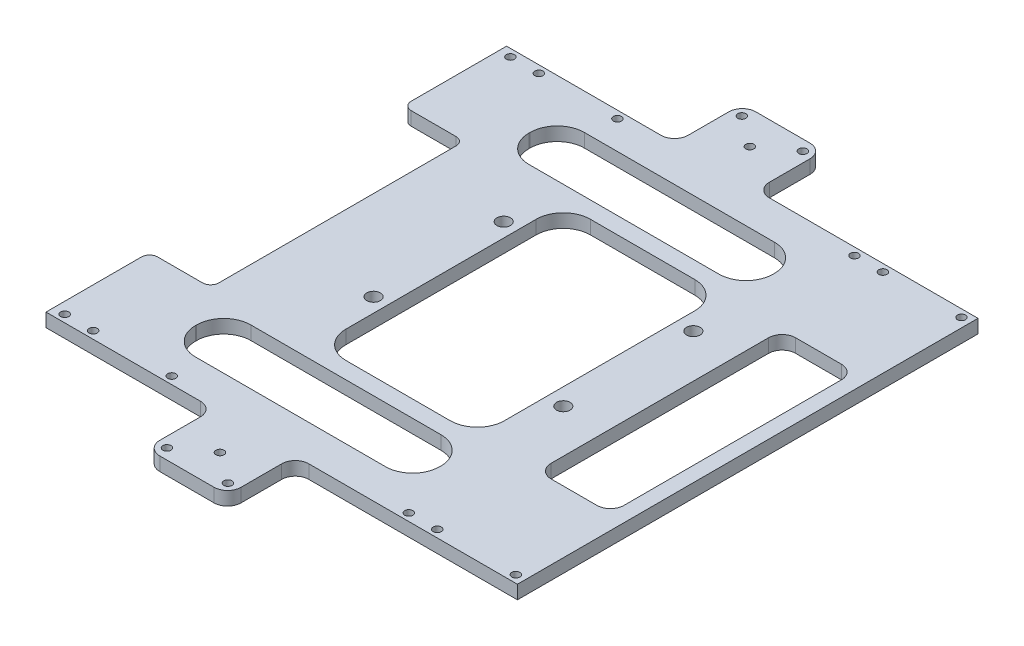
SolidWorks part; units mm, degrees
ref_plane "前视基准面" through (0, 0, 0) normal (0, 0, 1) x (1, 0, 0)
ref_plane "上视基准面" through (0, 0, 0) normal (0, 1, 0) x (1, 0, 0)
ref_plane "右视基准面" through (0, 0, 0) normal (1, 0, 0) x (0, 0, -1)
other "Configuration Table"
sketch "草图1" plane through (0, 0, 0) normal (0, 1, 0) x (1, 0, 0)
  line L0 (0, 0) -> (179.4567, 0) construction
  line L1 (-150, 150) -> (150, 150) construction
  line L2 (-150, 150) -> (-150, -150) construction
  line L3 (-150, -150) -> (150, -150) construction
  line L4 (150, 150) -> (150, -150) construction
  line L5 (-150, 150) -> (150, -150) construction
  line L6 (-150, -150) -> (150, 150) construction
  line L7 (-125, 85) -> (-67.9992, 85)
  line L9 (-125, -85) -> (-67.9992, -85)
  line L11 (-125, 85) -> (-125, 46.7806)
  line L16 (-111.5, 85) -> (-111.5, -49915) construction
  line L17 (-27.9992, 85) -> (49.0008, 85)
  line L29 (-62.9992, 90) -> (-62.9992, 105)
  line L30 (-57.9992, 110) -> (-37.9992, 110)
  line L31 (-32.9992, 90) -> (-32.9992, 105)
  line L32 (-32.9992, -90) -> (-32.9992, -105)
  line L33 (-57.9992, -110) -> (-37.9992, -110)
  line L34 (-62.9992, -90) -> (-62.9992, -105)
  line L35 (-27.9992, -85) -> (49.0008, -85)
  line L44 (15.5008, 96) -> (15.5008, -352.075) construction
  line L46 (-144.9992, -88.2675) -> (-77.9992, -88.2675) construction
  line L47 (-144.9992, -88.2675) -> (-144.9992, -128.3094) construction
  line L48 (-144.9992, -128.3094) -> (-77.9992, -128.3094) construction
  line L49 (-77.9992, -88.2675) -> (-77.9992, -128.3094) construction
  line L57 (-77.9992, 88.2675) -> (-77.9992, 128.3094) construction
  line L58 (-144.9992, 128.3094) -> (-77.9992, 128.3094) construction
  line L59 (-144.9992, 88.2675) -> (-144.9992, 128.3094) construction
  line L60 (-144.9992, 88.2675) -> (-77.9992, 88.2675) construction
  line L61 (-17.9992, -88.2675) -> (-17.9992, -128.3) construction
  line L62 (49.0008, -128.3) -> (-17.9992, -128.3) construction
  line L63 (49.0008, 128.3) -> (-17.9992, 128.3) construction
  line L64 (49.0008, 88.2675) -> (-17.9992, 88.2675) construction
  line L65 (49.0008, 88.2675) -> (49.0008, 128.3) construction
  line L66 (49.0008, 128.3) -> (-17.9992, 128.3) construction
  line L67 (-17.9992, 88.2675) -> (-17.9992, 128.3) construction
  line L68 (49.0008, -88.2675) -> (49.0008, -128.3) construction
  line L69 (49.0008, -88.2675) -> (-17.9992, -88.2675) construction
  line L71 (-47.9992, 110) -> (-47.9992, -134.4619) construction
  line L72 (49.0008, 85) -> (49.0008, -85)
  line L73 (-12.9149, -51.3108) -> (-83.0835, -51.3108)
  line L74 (-12.9149, 71.7703) -> (-83.0835, 71.7703)
  line L75 (-2.9149, 61.7703) -> (-2.9149, 61.3108)
  line L76 (-12.9149, 51.3108) -> (-83.0835, 51.3108)
  line L77 (-93.0835, 61.7703) -> (-93.0835, 61.3108)
  line L78 (-93.0835, -61.7703) -> (-93.0835, -61.3108)
  line L79 (-2.9149, -61.7703) -> (-2.9149, -61.3108)
  line L80 (-12.9149, -71.7703) -> (-83.0835, -71.7703)
  line L81 (-69.4223, 28.3555) -> (-69.4223, -19.6445) construction
  line L82 (-15.666, 45.1305) -> (-54.2, 45.1305)
  line L83 (-5.666, 35.1305) -> (-5.666, -35.1305)
  line L84 (-15.666, -45.1305) -> (-54.2, -45.1305)
  line L85 (-64.2, 35.1305) -> (-64.2, -35.1305)
  line L86 (-69.4223, -19.6445) -> (0.5777, -19.6445) construction
  line L87 (0.5777, -19.6445) -> (0.5777, 28.3555) construction
  line L88 (0.5777, 28.3555) -> (-69.4223, 28.3555) construction
  line L89 (-125, 46.7806) -> (-102.4346, 46.7806)
  line L90 (-102.4346, 46.7806) -> (-102.4346, -46.7806)
  line L91 (-125, -46.7806) -> (-102.4346, -46.7806)
  line L92 (-125, -46.7806) -> (-125, -85)
  circle A3 centre (-120.84, -82.25) radius 1.5
  circle A4 centre (-110.34, -82.25) radius 1.5
  circle A5 centre (-81.34, -82.25) radius 1.5
  circle A6 centre (-81.34, 82.25) radius 1.5
  circle A7 centre (-110.34, 82.25) radius 1.5
  circle A8 centre (-120.84, 82.25) radius 1.5
  arc A9 (-37.9992, 110) -> (-32.9992, 105) centre (-37.9992, 105) cw
  arc A10 (-62.9992, 105) -> (-57.9992, 110) centre (-57.9992, 105) cw
  arc A11 (-27.9992, 85) -> (-32.9992, 90) centre (-27.9992, 90) cw
  arc A12 (-67.9992, 85) -> (-62.9992, 90) centre (-67.9992, 90) ccw
  arc A13 (-67.9992, -85) -> (-62.9992, -90) centre (-67.9992, -90) cw
  arc A14 (-27.9992, -85) -> (-32.9992, -90) centre (-27.9992, -90) ccw
  arc A15 (-62.9992, -105) -> (-57.9992, -110) centre (-57.9992, -105) ccw
  arc A16 (-37.9992, -110) -> (-32.9992, -105) centre (-37.9992, -105) ccw
  circle A17 centre (6.16, 82.25) radius 1.5
  circle A18 centre (16.66, 82.25) radius 1.5
  circle A19 centre (45.66, 82.25) radius 1.5
  circle A20 centre (6.16, -82.25) radius 1.5
  circle A21 centre (16.66, -82.25) radius 1.5
  circle A22 centre (45.66, -82.25) radius 1.5
  circle A23 centre (-69.4223, 28.3555) radius 2.5
  circle A24 centre (0.5777, 28.3555) radius 2.5
  circle A25 centre (-69.4223, -19.6445) radius 2.5
  circle A26 centre (0.5777, -19.6445) radius 2.5
  circle A27 centre (-59.2492, -106.1) radius 1.5
  circle A28 centre (-36.7492, -106.1) radius 1.5
  circle A29 centre (-47.9992, -97.7894) radius 1.5
  circle A30 centre (-36.7492, 106.1) radius 1.5
  circle A31 centre (-59.2492, 106.1) radius 1.5
  circle A32 centre (-47.9992, 97.7894) radius 1.5
  arc A33 (-83.0835, 51.3108) -> (-93.0835, 61.3108) centre (-83.0835, 61.3108) cw
  arc A34 (-2.9149, 61.3108) -> (-12.9149, 51.3108) centre (-12.9149, 61.3108) cw
  arc A35 (-12.9149, 71.7703) -> (-2.9149, 61.7703) centre (-12.9149, 61.7703) cw
  arc A36 (-83.0835, 71.7703) -> (-93.0835, 61.7703) centre (-83.0835, 61.7703) ccw
  arc A37 (-83.0835, -51.3108) -> (-93.0835, -61.3108) centre (-83.0835, -61.3108) ccw
  arc A38 (-83.0835, -71.7703) -> (-93.0835, -61.7703) centre (-83.0835, -61.7703) cw
  arc A39 (-2.9149, -61.3108) -> (-12.9149, -51.3108) centre (-12.9149, -61.3108) ccw
  arc A40 (-12.9149, -71.7703) -> (-2.9149, -61.7703) centre (-12.9149, -61.7703) ccw
  arc A41 (-5.666, -35.1305) -> (-15.666, -45.1305) centre (-15.666, -35.1305) cw
  arc A42 (-54.2, -45.1305) -> (-64.2, -35.1305) centre (-54.2, -35.1305) cw
  arc A43 (-54.2, 45.1305) -> (-64.2, 35.1305) centre (-54.2, 35.1305) ccw
  arc A44 (-15.666, 45.1305) -> (-5.666, 35.1305) centre (-15.666, 35.1305) cw
  point P0 (0, 0)
  point P30 (-32.9992, 110)
  point P33 (-62.9992, 110)
  point P61 (-62.9992, -110)
  point P62 (-32.9992, -110)
  point P156 (-102.4346, 0)
  dimension "D7" = 3
  dimension "D12" = 5
  dimension "D17" = 22.5
  dimension "D19" = 3
  dimension "D22" = 10
  dimension "D23" = 10
  dimension "D1" = 300
  dimension "D2" = 300
  dimension "D3" = 65
  dimension "D4" = 50
  dimension "D5" = 2.75
  dimension "D6" = 4.16
  dimension "D8" = 10.5
  dimension "D9" = 29
  dimension "D10" = 30
  dimension "D11" = 15
  dimension "D13" = 67
  dimension "D14" = 9.34
  dimension "D15" = 2
  dimension "D16" = 15
  dimension "D18" = 15
  dimension "D20" = 3.9
  dimension "D21" = 8.3106
  dimension "D24" = 48
  dimension "D25" = 70
extrude "凸台-拉伸1" add sketch "草图1" along normal blind 5
sketch "草图2" plane through (0, 0, 0) normal (0, -1, 0) x (1, 0, 0)
  line L1 (21.5563, 45.1305) -> (38.4643, 45.1305)
  line L2 (16.5563, 40.1305) -> (16.5563, -40.1305)
  line L3 (21.5563, -45.1305) -> (38.4643, -45.1305)
  line L4 (43.4643, 40.1305) -> (43.4643, -40.1305)
  arc A0 (38.4643, -45.1305) -> (43.4643, -40.1305) centre (38.4643, -40.1305) ccw
  arc A1 (16.5563, -40.1305) -> (21.5563, -45.1305) centre (21.5563, -40.1305) ccw
  arc A2 (38.4643, 45.1305) -> (43.4643, 40.1305) centre (38.4643, 40.1305) cw
  arc A3 (21.5563, 45.1305) -> (16.5563, 40.1305) centre (21.5563, 40.1305) ccw
  dimension "D1" = 5
extrude "切除-拉伸1" cut sketch "草图2" against normal through all
fillet "圆角1" radius 3 4 edges at (-125, 2.5, -46.7806) (-125, 2.5, 46.7806) (-102.4346, 2.5, 46.7806) (-102.4346, 2.5, -46.7806)
